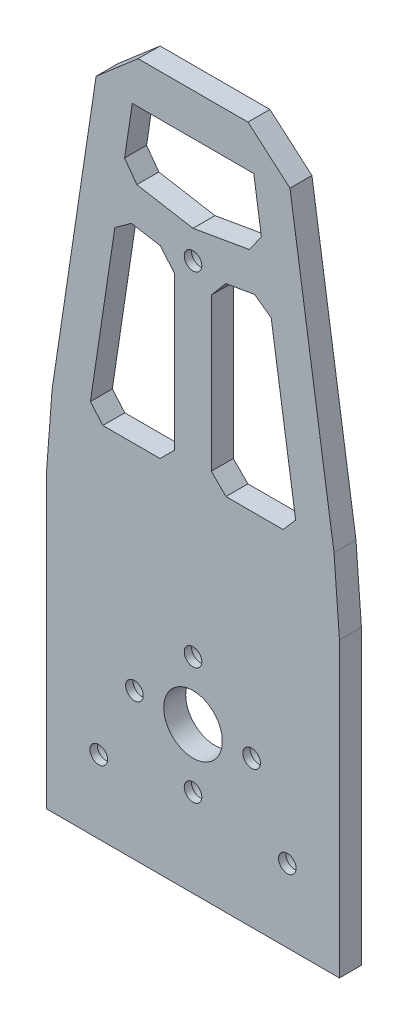
SolidWorks part; units mm, degrees
ref_plane "Front" through (0, 0, 0) normal (0, 0, 1) x (1, 0, 0)
ref_plane "Top" through (0, 0, 0) normal (0, 1, 0) x (1, 0, 0)
ref_plane "Right" through (0, 0, 0) normal (1, 0, 0) x (0, 0, -1)
sketch "草图1" plane through (0, 0, 0) normal (0, 0, 1) x (1, 0, 0)
  line L0 (20, 5) -> (20, 45)
  line L1 (-7.5, 100) -> (-13.2417, 95.0553)
  line L2 (-13.2417, 95.0553) -> (-19.2583, 54.9447)
  line L3 (7.5, 100) -> (13.2417, 95.0553)
  line L4 (-20, 5) -> (-20, 45)
  line L5 (7.5, 100) -> (-7.5, 100)
  line L6 (13.2417, 95.0553) -> (19.2583, 54.9447)
  line L7 (-19.2583, 54.9447) -> (-20, 45)
  line L8 (5.5, -100) -> (-5.5, -100)
  line L9 (-7.7481, -98.0154) -> (-19.3798, -4.9614)
  line L10 (19.3798, -4.9614) -> (7.7481, -98.0154)
  line L11 (19.2583, 54.9447) -> (20, 45)
  line L12 (-19.3798, -4.9614) -> (-20, 5)
  line L13 (19.3798, -4.9614) -> (20, 5)
  line L14 (-5.5, -100) -> (-7.7481, -98.0154)
  line L15 (7.7481, -98.0154) -> (5.5, -100)
  point P1 (-20, 50)
  point P3 (-20, 0)
  point P5 (20, 0)
  point P6 (20, 50)
  point P8 (12.5, 100)
  point P9 (-12.5, 100)
  point P10 (7.5, -100)
  point P12 (-7.5, -100)
extrude "凸台-拉伸1" add sketch "草图1" along normal blind 3
sketch "草图2" plane through (0, 0, 3) normal (0, 0, 1) x (1, 0, 0)
  line L0 (0, 0) -> (0, -100) construction
  line L1 (-5.5, -100) -> (5.5, -100) construction
  line L2 (10, -5) -> (-10, -5)
  line L3 (-10, -5) -> (0, -22.3205)
  line L4 (0, -22.3205) -> (10, -5)
  line L5 (-5.5, -100) -> (5.5, -100) construction
  line L12 (2.7867, -97.3953) -> (14.4184, -4.3412)
  line L13 (6.2111, -70) -> (13.9389, -8.1777)
  line L14 (-13.9389, -8.1777) -> (-2.5, -27.9904)
  line L15 (-14.4184, -4.3412) -> (-2.7867, -97.3953)
  line L16 (-13.9389, -8.1777) -> (-6.2111, -70)
  line L17 (2.5, -27.9904) -> (13.9389, -8.1777)
  line L18 (6.2111, -70) -> (2.5, -70)
  line L19 (2.5, -27.9904) -> (2.5, -70)
  line L20 (2.5, 0) -> (2.5, -100) construction
  line L21 (4.3301, -24.8205) -> (14.3301, -7.5) construction
  line L22 (10, -70) -> (-10, -70) construction
  line L23 (-2.5, -27.9904) -> (-2.5, -70)
  line L24 (-14.3301, -7.5) -> (-4.3301, -24.8205) construction
  line L25 (-2.5, -70) -> (-6.2111, -70)
  line L26 (2.5, -90) -> (2.5, -80)
  line L27 (2.5, -90) -> (-2.5, -90)
  line L29 (2.5, -80) -> (-2.5, -80)
  line L30 (-2.5, -90) -> (-2.5, -80)
  point P8 (0, -5)
  point P34 (0, -90)
  point P35 (0, -80)
  dimension "D1" = 5
  dimension "D2" = 5
  dimension "D9" = 10
  dimension "D3" = 5
  dimension "D4" = 5
  dimension "D5" = 5
  dimension "D6" = 65
  dimension "D7" = 2.5
  dimension "D8" = 5
extrude "切除-拉伸1" cut sketch "草图2" against normal up to next
sketch "草图3" plane through (0, 0, 0) normal (0, 0, -1) x (-1, 0, 0)
  point P0 (-5.5861, -75)
  point P1 (5.5861, -75)
hole_wizard "M2 凹头盖螺钉的柱形沉头孔1" positions "3D草图1" profile "草图4" counterbore size "M2" standard "ANSI Metric" end condition through all
sketch3d "3D草图1"
  point P0 (5.5861, -75, 0)
  point P3 (-5.5861, -75, 0)
sketch "草图4" plane through (5.5861, -75, 0) normal (1, 0, 0) x (0, 1, 0)
  line L0 (0, 0) -> (0, 3)
  line L1 (0, 3) -> (1.2, 3)
  line L3 (1.2, 3) -> (1.2, 2)
  line L4 (1.2, 2) -> (2.2, 2)
  line L5 (2.2, 2) -> (2.2, 0)
  line L7 (2.2, 0) -> (0, 0)
  line L11 (0, -6.35) -> (0, 107.95) construction
  dimension "通孔孔直径" = 2.4
  dimension "通孔孔深度" = 3
  dimension "柱形沉头孔直径" = 4.4
  dimension "柱形沉头孔深度" = 2
sketch "草图5" plane through (0, 0, 0) normal (0, 0, -1) x (-1, 0, 0)
  line L0 (-20, 25) -> (20, 25) construction
  line L1 (-20, 5) -> (-20, 45) construction
  line L2 (20, 45) -> (20, 5) construction
  circle A0 centre (0, 25) radius 4
extrude "切除-拉伸2" cut sketch "草图5" against normal up to next
sketch "草图6" plane through (0, 0, 0) normal (0, 0, -1) x (-1, 0, 0)
  point P0 (-8, 25)
  point P1 (0, 33)
  point P2 (8, 25)
  point P3 (0, 17)
  point P4 (0, 25)
  dimension "D1" = 8
  dimension "D2" = 8
  dimension "D3" = 8
  dimension "D4" = 8
hole_wizard "M2 凹头盖螺钉的柱形沉头孔2" positions "3D草图2" profile "草图7" counterbore size "M2" standard "ANSI Metric" end condition through all
sketch3d "3D草图2"
  point P0 (8, 25, 0)
  point P3 (0, 33, 0)
  point P6 (-8, 25, 0)
  point P9 (0, 17, 0)
sketch "草图7" plane through (8, 25, 0) normal (1, 0, 0) x (0, 1, 0)
  line L0 (0, 0) -> (0, 3)
  line L1 (0, 3) -> (1.2, 3)
  line L3 (1.2, 3) -> (1.2, 2)
  line L4 (1.2, 2) -> (2.2, 2)
  line L5 (2.2, 2) -> (2.2, 0)
  line L7 (2.2, 0) -> (0, 0)
  line L11 (0, -6.35) -> (0, 107.95) construction
  dimension "通孔孔直径" = 2.4
  dimension "通孔孔深度" = 3
  dimension "柱形沉头孔直径" = 4.4
  dimension "柱形沉头孔深度" = 2
sketch "草图8" plane through (0, 0, 0) normal (0, 0, -1) x (-1, 0, 0)
  line L0 (0, -3.3014) -> (0, -6.7473) construction
  point P2 (12.88, -5.0117)
  point P3 (-12.88, 14.9883)
  point P4 (12.88, 14.9883)
  point P12 (-12.88, -5.0117)
  dimension "D1" = 20
  dimension "D2" = 20
hole_wizard "M2 凹头盖螺钉的柱形沉头孔3" positions "3D草图3" profile "草图9" counterbore size "M2" standard "ANSI Metric" end condition through all
sketch3d "3D草图3"
  point P0 (12.88, -5.0117, 0)
  point P3 (-12.88, -5.0117, 0)
sketch "草图9" plane through (12.88, -5.0117, 0) normal (1, 0, 0) x (0, 1, 0)
  line L0 (0, 0) -> (0, 3)
  line L1 (0, 3) -> (1.2, 3)
  line L3 (1.2, 3) -> (1.2, 2)
  line L4 (1.2, 2) -> (2.2, 2)
  line L5 (2.2, 2) -> (2.2, 0)
  line L7 (2.2, 0) -> (0, 0)
  line L11 (0, -6.35) -> (0, 107.95) construction
  dimension "通孔孔直径" = 2.4
  dimension "通孔孔深度" = 3
  dimension "柱形沉头孔直径" = 4.4
  dimension "柱形沉头孔深度" = 2
sketch "草图10" plane through (0, 0, 0) normal (0, 0, -1) x (-1, 0, 0)
  line L0 (-9.5291, 85.3364) -> (-1.6465, 83.9709) construction
  line L1 (9.5291, 85.3364) -> (1.6465, 83.9709) construction
  line L2 (-14.3136, 54.203) -> (-8.297, 94.3136)
  line L3 (-14.0169, 56.1809) -> (-10.6793, 78.4319)
  line L4 (-9.344, 87.3336) -> (-8.297, 94.3136)
  line L5 (8.297, 94.3136) -> (14.3136, 54.203)
  line L6 (8.297, 94.3136) -> (9.344, 87.3336)
  line L7 (-8.297, 94.3136) -> (0, 94.3136)
  line L8 (-12.3136, 54.203) -> (-4.5, 54.203)
  line L9 (0, 95.3482) -> (0, 43.337) construction
  line L10 (-2.5, 77.0442) -> (-2.5, 56.203)
  line L11 (-9.344, 87.3336) -> (-7.6701, 85.0144)
  line L12 (9.344, 87.3336) -> (7.6701, 85.0144)
  line L13 (-10.3826, 80.4098) -> (-2.5, 79.0442) construction
  line L14 (-10.6793, 78.4319) -> (-8.4119, 80.0684)
  line L15 (4.5, 54.203) -> (12.3136, 54.203)
  line L16 (-8.4119, 80.0684) -> (-4.4706, 79.3856)
  line L17 (8.4119, 80.0684) -> (4.4706, 79.3856)
  line L18 (-7.6701, 85.0144) -> (0, 83.6856)
  line L19 (7.6701, 85.0144) -> (0, 83.6856)
  line L20 (0, 94.3136) -> (8.297, 94.3136)
  line L21 (-4.4706, 79.3856) -> (-2.5, 77.0442)
  line L22 (2.5, 77.0442) -> (2.5, 56.203)
  line L23 (10.6793, 78.4319) -> (14.0169, 56.1809)
  line L24 (10.3826, 80.4098) -> (2.5, 79.0442) construction
  line L25 (4.4706, 79.3856) -> (2.5, 77.0442)
  line L26 (10.6793, 78.4319) -> (8.4119, 80.0684)
  line L27 (-12.3136, 54.203) -> (-14.0169, 56.1809)
  line L28 (-4.5, 54.203) -> (-2.5, 56.203)
  line L29 (2.5, 56.203) -> (4.5, 54.203)
  line L30 (12.3136, 54.203) -> (14.0169, 56.1809)
  point P16 (-2.5, 54.203)
  point P17 (2.5, 54.203)
  point P18 (-10.3826, 80.4098)
  point P26 (-9.6407, 85.3557)
  point P28 (9.6407, 85.3557)
  dimension "D3" = 26.5
  dimension "D6" = 5
  dimension "D1" = 5
  dimension "D2" = 5
  dimension "D7" = 5
extrude "切除-拉伸3" cut sketch "草图10" against normal blind 3
sketch "草图11" plane through (0, 0, 0) normal (0, 0, -1) x (-1, 0, 0)
  point P11 (0, 79.8401)
hole_wizard "M2 凹头盖螺钉的柱形沉头孔5" positions "3D草图5" profile "草图13" counterbore size "M2" standard "ANSI Metric" end condition through all
sketch3d "3D草图5"
  point P0 (0, 79.8401, 0)
sketch "草图13" plane through (0, 79.8401, 0) normal (1, 0, 0) x (0, 1, 0)
  line L0 (0, 0) -> (0, 3)
  line L1 (0, 3) -> (1.2, 3)
  line L3 (1.2, 3) -> (1.2, 2)
  line L4 (1.2, 2) -> (2.2, 2)
  line L5 (2.2, 2) -> (2.2, 0)
  line L7 (2.2, 0) -> (0, 0)
  line L11 (0, -6.35) -> (0, 107.95) construction
  dimension "通孔孔直径" = 2.4
  dimension "通孔孔深度" = 3
  dimension "柱形沉头孔直径" = 4.4
  dimension "柱形沉头孔深度" = 2
hole_wizard "M2 凹头盖螺钉的柱形沉头孔6" positions "3D草图8" profile "草图16" counterbore size "M2" standard "ANSI Metric" end condition up to next
sketch3d "3D草图8"
  point P0 (12.88, 14.9883, 0)
  point P3 (-12.88, 14.9883, 0)
sketch "草图16" plane through (12.88, 14.9883, 0) normal (1, 0, 0) x (0, 1, 0)
  line L0 (0, 0) -> (0, 3)
  line L1 (0, 3) -> (1.2, 3)
  line L3 (1.2, 3) -> (1.2, 2)
  line L4 (1.2, 2) -> (2.2, 2)
  line L5 (2.2, 2) -> (2.2, 0)
  line L7 (2.2, 0) -> (0, 0)
  line L11 (0, -6.35) -> (0, 107.95) construction
  dimension "通孔孔直径" = 2.4
  dimension "通孔孔深度" = 3
  dimension "柱形沉头孔直径" = 4.4
  dimension "柱形沉头孔深度" = 2
sketch "草图17" plane through (0, 0, 0) normal (0, 0, -1) x (-1, 0, 0)
  line L0 (-20, 5) -> (20, 5)
  line L1 (-20, 5) -> (-20, 99.9983)
  line L2 (20, 5) -> (20, 99.9983)
  line L3 (-7.5, 100) -> (7.5, 100) construction
  line L4 (20, 5) -> (19.3798, -4.9614) construction
  line L5 (-7.5, 100) -> (7.5, 100)
  line L6 (-7.5, 100) -> (-20, 99.9983)
  line L7 (7.5, 100) -> (20, 99.9983)
extrude "切除-拉伸4" cut sketch "草图17" against normal blind 10 flip side to cut
